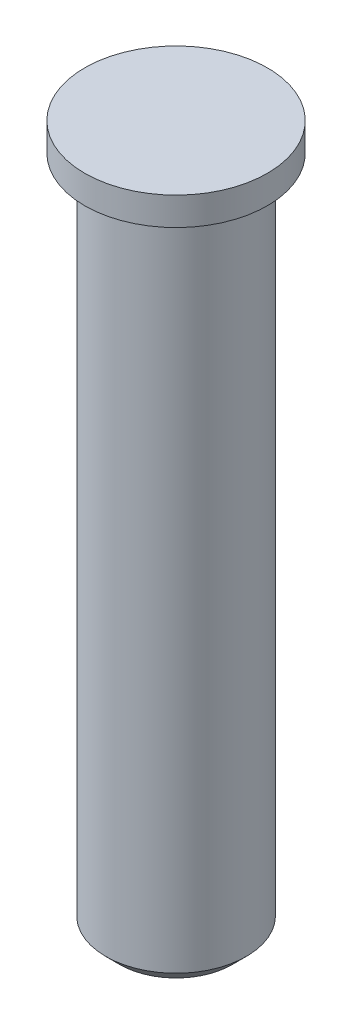
SolidWorks part; units mm, degrees
material "acero"
ref_plane "Alzado" through (0, 0, 0) normal (0, 0, 1) x (1, 0, 0)
ref_plane "Planta" through (0, 0, 0) normal (0, 1, 0) x (1, 0, 0)
ref_plane "Vista lateral" through (0, 0, 0) normal (1, 0, 0) x (0, 0, -1)
sketch "Croquis1" plane through (0, 0, 0) normal (0, 0, 1) x (1, 0, 0)
  line L0 (0, 0) -> (0, -60.9498) construction
  line L1 (0, 0) -> (3.25, 0)
  line L2 (3.25, 0) -> (3.25, -1)
  line L3 (3.25, -1) -> (2.5, -1)
  line L4 (2.5, -1) -> (2.5, -25)
  line L5 (2.5, -25) -> (0, -25)
  line L6 (0, -25) -> (0, 0)
  dimension "D1" = 25
  dimension "D2" = 1
  dimension "D3" = 6.5
  dimension "D4" = 5
revolve "Revolución1" add sketch "Croquis1" angle 360 about L0
chamfer "Chaflán1" distance 0.5 angle 45 1 edges at (0, -25, 2.5)
